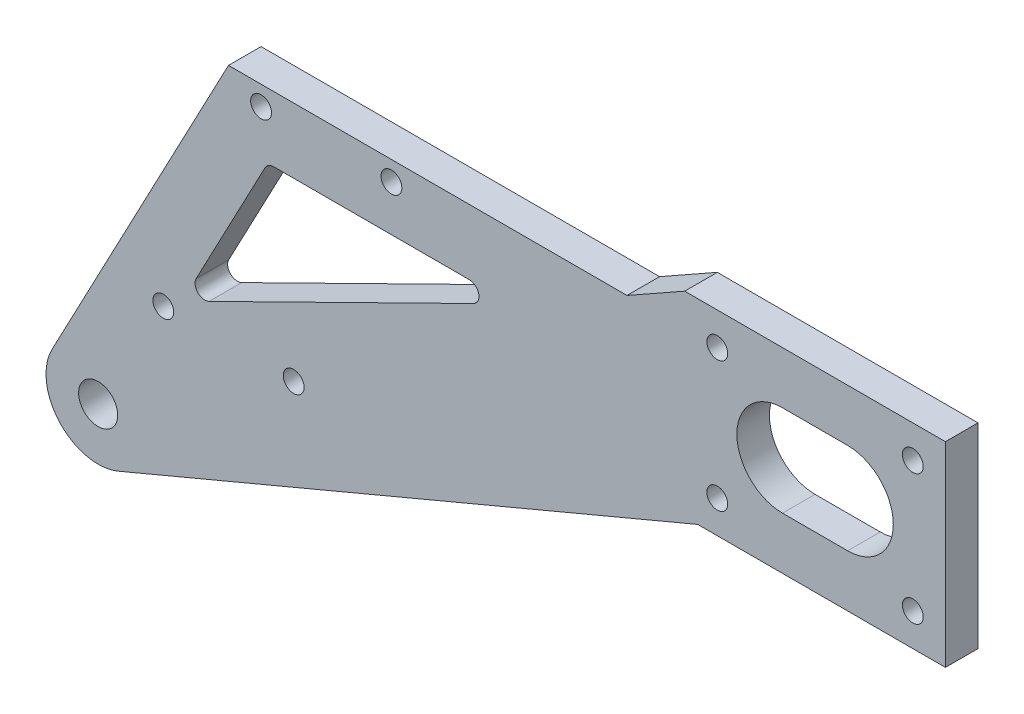
SolidWorks part; units mm, degrees
material "Thornel Mat VMA"
ref_plane "前视基准面" through (0, 0, 0) normal (0, 0, 1) x (1, 0, 0)
ref_plane "上视基准面" through (0, 0, 0) normal (0, 1, 0) x (1, 0, 0)
ref_plane "右视基准面" through (0, 0, 0) normal (1, 0, 0) x (0, 0, -1)
sketch "草图1" plane through (0, 0, 0) normal (0, 0, 1) x (1, 0, 0)
  line L0 (-3.9331, 6.9664) -> (90, 60)
  line L1 (90, 60) -> (130, 60)
  line L2 (130, 60) -> (130, 30)
  line L3 (92, 30) -> (3.1005, -7.3748)
  line L4 (92, 30) -> (130, 30)
  line L5 (125, 55) -> (95, 55) construction
  line L6 (125, 55) -> (125, 35) construction
  line L7 (125, 35) -> (95, 35) construction
  line L8 (95, 55) -> (95, 35) construction
  circle A0 centre (0, 0) radius 3
  arc A1 (-3.9331, 6.9664) -> (3.1005, -7.3748) centre (0, 0) ccw
  circle A2 centre (95, 55) radius 1.6
  circle A3 centre (125, 55) radius 1.6
  circle A4 centre (125, 35) radius 1.6
  circle A5 centre (95, 35) radius 1.6
  dimension "D1" = 6
  dimension "D2" = 40
  dimension "D6" = 8
  dimension "D7" = 5
  dimension "D11" = 3.2
  dimension "D3" = 30
  dimension "D4" = 60
  dimension "D5" = 90
  dimension "D8" = 5
  dimension "D9" = 5
  dimension "D10" = 5
  dimension "D12" = 3
extrude "凸台-拉伸1" add sketch "草图1" along normal blind 5
sketch "草图3" plane through (0, 0, 5) normal (0, 0, 1) x (1, 0, 0)
  line L0 (81.144, 55) -> (20, 55)
  line L1 (90, 60) -> (-3.9331, 6.9664) construction
  line L2 (20, 55) -> (20, 20.4788)
  line L3 (20, 20.4788) -> (81.144, 55)
  line L4 (92, 30) -> (130, 30) construction
  circle A0 centre (95, 55) radius 1.6 construction
  dimension "D1" = 25
  dimension "D2" = 75
extrude "凸台-拉伸2" add sketch "草图3" against normal up to surface (5 mm away) up to face at (72.4002, 29.3788, 0)
sketch "草图4" plane through (0, 0, 5) normal (0, 0, 1) x (1, 0, 0)
  line L0 (25, 52) -> (45, 52) construction
  line L1 (81.144, 55) -> (20, 55) construction
  circle A0 centre (25, 52) radius 1.6
  circle A1 centre (45, 52) radius 1.6
  circle A2 centre (95, 55) radius 1.6 construction
  dimension "D1" = 3
  dimension "D4" = 3.2
  dimension "D2" = 20
  dimension "D3" = 50
extrude "切除-拉伸1" cut sketch "草图4" against normal through all
sketch "草图6" plane through (0, 0, 5) normal (0, 0, 1) x (1, 0, 0)
  line L0 (-7.074, 3.736) -> (20, 55)
  line L1 (20, 55) -> (20, 20.4788) construction
  line L2 (20, 20.4788) -> (-3.9331, 6.9664) construction
  line L3 (20, 55) -> (20, 20.4788)
  line L4 (20, 20.4788) -> (-3.9331, 6.9664)
  arc A0 (-3.9331, 6.9664) -> (3.1005, -7.3748) centre (0, 0) ccw construction
  arc A1 (-3.9331, 6.9664) -> (-7.074, 3.736) centre (0, 0) ccw
extrude "凸台-拉伸3" add sketch "草图6" against normal up to surface (5 mm away) up to face at (26.6, 52, 0)
sketch "草图5" plane through (0, 0, 5) normal (0, 0, 1) x (1, 0, 0)
  line L3 (20, 55) -> (-7.074, 3.736) construction
  line L10 (81.144, 55) -> (20, 55) construction
  line L11 (105, 45) -> (115, 45) construction
  line L12 (95, 55) -> (125, 55) construction
  line L13 (95, 55) -> (95, 35) construction
  line L14 (95, 35) -> (125, 35) construction
  line L15 (125, 55) -> (125, 35) construction
  line L16 (105, 52) -> (115, 52)
  line L17 (105, 38) -> (115, 38)
  line L21 (25.6054, 44.2005) -> (15.0428, 24.2005)
  line L22 (17.0325, 22.1546) -> (57.5951, 42.1546)
  line L24 (56.9318, 45) -> (26.9318, 45)
  arc A11 (105, 52) -> (105, 38) centre (105, 45) ccw
  arc A12 (115, 38) -> (115, 52) centre (115, 45) ccw
  arc A13 (57.5951, 42.1546) -> (56.9318, 45) centre (56.9318, 43.5) ccw
  arc A14 (15.0428, 24.2005) -> (17.0325, 22.1546) centre (16.3692, 23.5) ccw
  arc A15 (25.6054, 44.2005) -> (26.9318, 45) centre (26.9318, 43.5) cw
  point P15 (0, 0)
  point P29 (110, 45)
  point P30 (110, 55)
  point P53 (95, 45)
  dimension "D3" = 10
  dimension "D10" = 7
  dimension "D4" = 1.5
  dimension "D8" = 30
  dimension "D2" = 10
  dimension "D11" = 10
  dimension "D12" = 20
extrude "切除-拉伸2" cut sketch "草图5" against normal through all
sketch "草图7" plane through (0, 0, 5) normal (0, 0, 1) x (1, 0, 0)
  line L0 (10, 18) -> (30, 18) construction
  circle A0 centre (10, 18) radius 1.6
  circle A1 centre (30, 18) radius 1.6
  dimension "D2" = 3.2
  dimension "D1" = 20
  dimension "D3" = 10
  dimension "D4" = 18
extrude "切除-拉伸3" cut sketch "草图7" against normal through all
